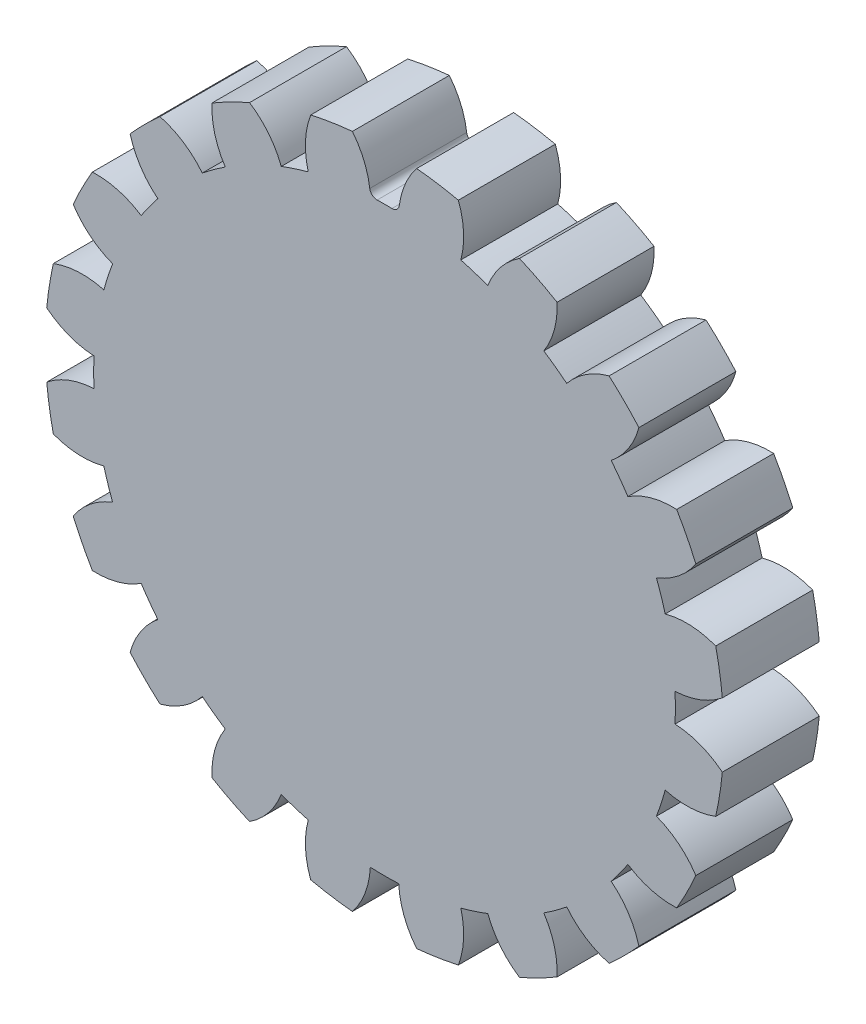
SolidWorks part; units mm, degrees
ref_plane "Front" through (0, 0, 0) normal (0, 0, 1) x (1, 0, 0)
ref_plane "Top" through (0, 0, 0) normal (0, 1, 0) x (1, 0, 0)
ref_plane "Right" through (0, 0, 0) normal (1, 0, 0) x (0, 0, -1)
sketch "Sketch1" plane through (0, 0, 0) normal (0, 0, 1) x (1, 0, 0)
  circle A0 centre (0, 0) radius 15
  circle A1 centre (0, 0) radius 17.5
  circle A2 centre (0, 0) radius 16.25
  dimension "D1" = 35
  dimension "D2" = 30
  dimension "D3" = 32.5
extrude "Boss-Extrude1" add sketch "Sketch1" along normal mid plane 5 contours A1
sketch "Sketch3" plane through (0, 0, 0) normal (0, 0, 1) x (1, 0, 0)
  line L0 (0, 0) -> (0, 17.5) construction
  line L1 (-0.9812, 16.2204) -> (0.9812, 16.2204) construction
  line L2 (-1.7796, 18.4142) -> (0, 13.5247) construction
  line L3 (0, 0) -> (2.1094, 17.3724) construction
  line L4 (0.9812, 16.2204) -> (2.9291, 15.9838) construction
  line L5 (0, 0) -> (-0.7315, 14.9822) construction
  circle A0 centre (0, 0) radius 17.5 construction
  arc A1 (-2.6391, 18.3108) -> (-0.7315, 14.9822) centre (-4.9488, 14.7762) cw
  arc A2 (2.6391, 18.3108) -> (0.7315, 14.9822) centre (4.9488, 14.7762) ccw
  arc A3 (0.7315, 14.9822) -> (-0.7315, 14.9822) centre (0, 0) ccw
  circle A4 centre (0, 0) radius 15 construction
  circle A6 centre (0, 0) radius 16.25 construction
  circle A7 centre (0, 0) radius 18.5
  arc A8 (2.6391, 18.3108) -> (-2.6391, 18.3108) centre (0, 0) ccw
  circle A9 centre (0, 0) radius 17.5 construction
  dimension "D3" = 6.923
  dimension "D2" = 20
  dimension "D1" = 1
extrude "Cut-Extrude1" cut sketch "Sketch3" against normal through all both and the other way through all
fillet "Fillet2" radius 0.375 2 edges at (0.7315, 14.9822, 0) (-0.7315, 14.9822, 0)
pattern_circular "CirPattern1" count 20 over 360 about axis through (0, 0, 0) along (0, 0, 1) of "Cut-Extrude1"
equation "\"od\" = 35'outside diameter"
equation "\"n\" = 26'number of teeth"
equation "\"m\"= \"od\" / ( \"n\" + 2 )'module"
equation "\"p\"= \"m\" * pi'pitch"
equation "\"d\"= \"m\" * \"n\"'primitive diameter"
equation "\"da\"= \"d\" + 2 * \"m\"'head diamater"
equation "\"df\"= \"d\" - 2 * \"m\"'foot diameter"
equation "\"D1@Sketch1\"=\"od\""
equation "\"D2@Sketch1\"=\"df\""
equation "\"D3@Sketch1\"=\"d\""
equation "\"D3@Sketch3\"=180/\"n\""
equation "\"D1@Fillet2\"=.3*\"m\""
